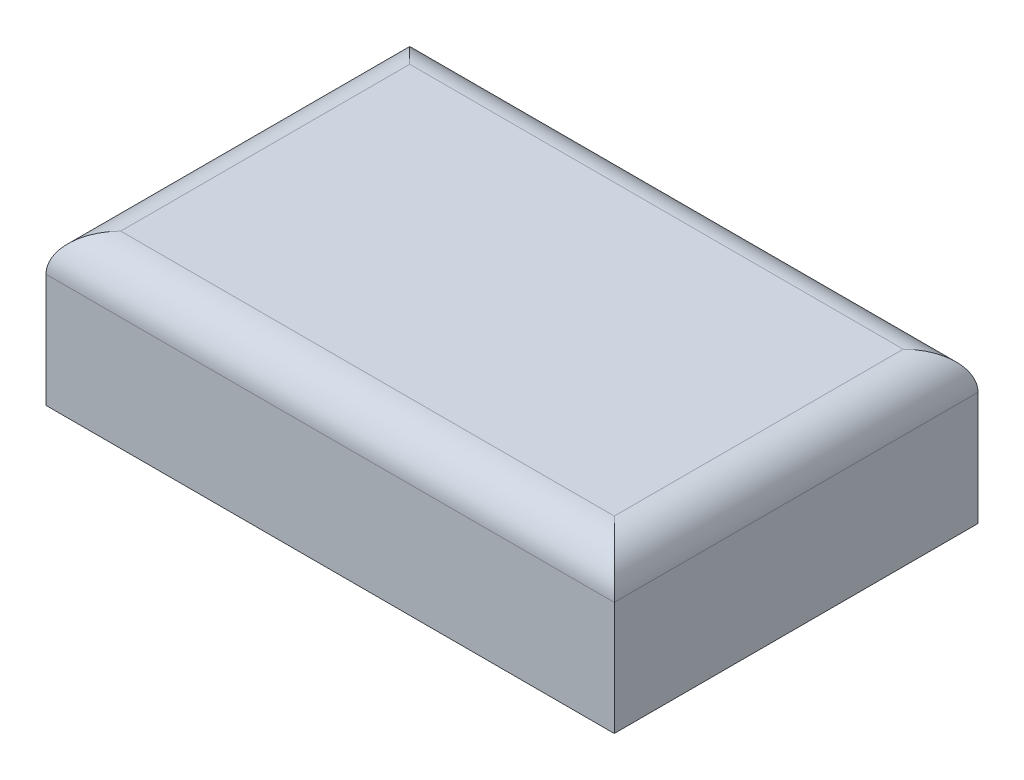
SolidWorks part; units mm, degrees
ref_plane "Front Plane" through (0, 0, 0) normal (0, 0, 1) x (1, 0, 0)
ref_plane "Top Plane" through (0, 0, 0) normal (0, 1, 0) x (1, 0, 0)
ref_plane "Right Plane" through (0, 0, 0) normal (1, 0, 0) x (0, 0, -1)
sketch "Sketch1" plane through (0, 0, 0) normal (0, 1, 0) x (1, 0, 0)
  line L1 (-68.2052, 12.2367) -> (7.8348, 12.2367)
  line L2 (-68.2052, 12.2367) -> (-68.2052, -36.4333)
  line L3 (-68.2052, -36.4333) -> (7.8348, -36.4333)
  line L4 (7.8348, 12.2367) -> (7.8348, -36.4333)
extrude "Boss-Extrude1" add sketch "Sketch1" along normal blind 20.2 contours L2 L1 L4 L3
fillet "Fillet3" radius 5 4 edges at (-30.1852, 20.2, 36.4333) (7.8348, 20.2, 12.0983) (-30.1852, 20.2, -12.2367) (-68.2052, 20.2, 12.0983)
